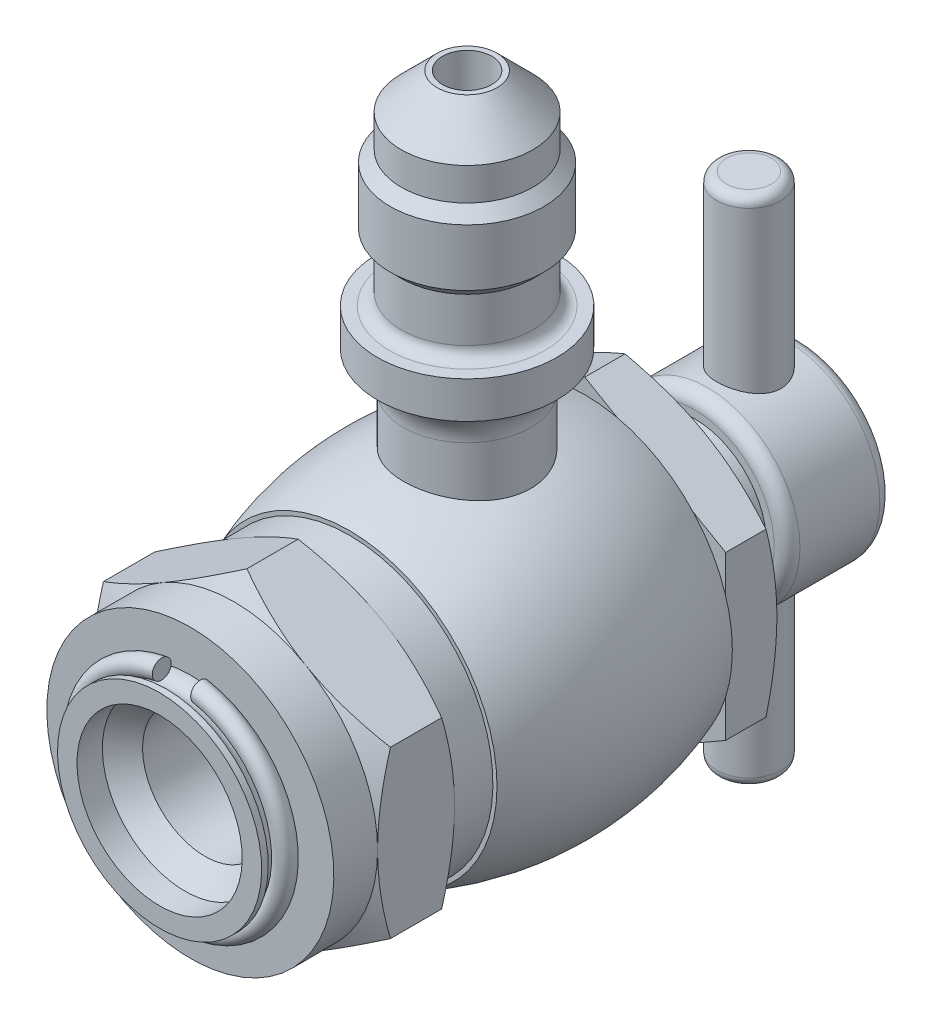
SolidWorks part; units mm, degrees
material "Brass"
ref_plane "Front Plane" through (0, 0, 0) normal (0, 0, 1) x (1, 0, 0)
ref_plane "Top Plane" through (0, 0, 0) normal (0, 1, 0) x (1, 0, 0)
ref_plane "Right Plane" through (0, 0, 0) normal (1, 0, 0) x (0, 0, -1)
sketch "Sketch1" plane through (0, 0, 0) normal (1, 0, 0) x (0, 0, -1)
  line L0 (-19.05, 0) -> (0, 0) construction
  line L1 (0, 0) -> (17.4625, 0) construction
  line L2 (0, 22.9425) -> (0, -22.9425) construction
  line L3 (4.7625, 22.9426) -> (-4.7625, 22.9426) construction
  line L5 (4.7625, 22.9426) -> (4.7625, 24.0009) construction
  line L8 (-3.937, 5.7468) -> (3.937, 5.7468)
  line L9 (5.5563, 8.0328) -> (5.5563, 10.3188)
  line L14 (5.5563, 8.0328) -> (-5.5562, 8.0328)
  line L16 (5.5563, 10.3188) -> (-5.5562, 10.3187)
  line L17 (-5.5562, 8.0328) -> (-5.5562, 10.3187)
  line L18 (0, 8.0328) -> (0, 5.7468) construction
  line L19 (3.937, 5.7468) -> (3.937, 2.8583) construction
  line L21 (19.4469, -22.9426) -> (15.4781, -22.9426)
  line L22 (19.4469, -22.9426) -> (19.4469, 8.8074)
  line L23 (15.4781, -22.9426) -> (15.4781, 8.8074)
  line L24 (19.4469, 8.8074) -> (15.4781, 8.8074)
  line L25 (-19.05, -0.9144) -> (-18.644, -0.9144)
  line L26 (20.6375, -12.6238) -> (20.6375, -1.5113) construction
  line L27 (20.6375, -1.5113) -> (14.097, -1.5113) construction
  line L28 (14.097, -1.5113) -> (14.097, -7.0676) construction
  line L29 (14.097, -7.0676) -> (11.557, -7.0675) construction
  line L30 (11.557, -7.0675) -> (11.557, -0.7179) construction
  line L31 (11.557, -0.7179) -> (9.7467, 2.921) construction
  line L32 (9.7467, 2.921) -> (7.2898, 2.921) construction
  line L33 (7.2898, 2.921) -> (7.2898, -7.239) construction
  line L34 (7.2898, -7.239) -> (-7.2898, -7.239) construction
  line L35 (-7.2898, -7.239) -> (-7.2898, 1.9037) construction
  line L36 (-7.2898, 1.9037) -> (7.2898, 1.9037) construction
  line L37 (-7.2898, -7.239) -> (-9.671, -7.239) construction
  line L38 (-9.671, -7.239) -> (-9.671, 1.651) construction
  line L39 (-9.671, 1.651) -> (-7.2898, 1.651) construction
  line L40 (-9.671, 1.651) -> (-14.4335, 1.651) construction
  line L41 (-14.4335, 1.651) -> (-17.145, 1.651)
  line L42 (-17.145, 1.651) -> (-17.145, -0.9144)
  line L45 (-19.05, -0.9144) -> (-19.05, -7.239)
  line L46 (-19.05, -0.9144) -> (-19.8437, -0.9144) construction
  line L47 (11.5252, 0) -> (-11.5252, 0) construction
  line L48 (0, 11.5252) -> (0, -11.5252) construction
  line L49 (14.097, -7.0676) -> (15.4781, -7.0676) construction
  line L50 (-17.4752, -2.1209) -> (-19.05, -2.1209)
  line L51 (-11.4808, -3.3655) -> (-11.4808, -4.8514)
  line L52 (-9.779, -4.8514) -> (-9.779, -6.35)
  line L53 (-8.1788, -7.239) -> (-8.1788, -6.35)
  line L54 (-8.1788, -6.35) -> (-9.779, -6.35)
  line L55 (-9.779, -4.8514) -> (-11.4808, -4.8514)
  line L56 (-11.4808, -3.3655) -> (-16.2306, -3.3655)
  line L57 (-16.2306, -3.3655) -> (-17.4752, -2.1209)
  line L58 (-8.1788, -7.239) -> (-19.05, -7.239) construction
  line L59 (-19.05, -7.239) -> (-19.05, -2.1209) construction
  line L60 (1.8542, 22.9426) -> (4.0751, 20.7217) construction
  line L61 (4.0751, 20.7217) -> (4.0751, 18.7074) construction
  line L62 (4.0751, 18.7074) -> (4.7625, 18.02) construction
  line L63 (4.7625, 18.02) -> (4.7625, 14.4977) construction
  line L64 (4.7625, 14.4977) -> (4.0751, 13.8103) construction
  line L65 (4.0751, 13.8103) -> (4.0751, 10.3188) construction
  line L66 (4.8771, 23.9347) -> (3.9605, 23.4056) construction
  line L67 (3.9605, 23.4056) -> (4.8771, 22.8764) construction
  line L68 (4.8771, 22.8764) -> (4.8771, 23.9347) construction
  line L69 (4.7625, 23.8686) -> (4.7625, 22.9426) construction
  line L70 (4.8771, 23.4056) -> (4.7625, 23.4056) construction
  line L71 (4.7625, 23.4056) -> (4.0751, 23.4056) construction
  line L72 (4.0751, 23.4056) -> (3.9605, 23.4056) construction
  line L73 (4.0751, 23.4717) -> (4.0751, 23.3394)
  line L74 (4.8198, 23.9017) -> (4.8198, 22.9095)
  line L75 (4.0751, 23.3394) -> (4.8198, 22.9095)
  line L76 (4.0751, 23.4717) -> (4.8198, 23.9017)
  line L77 (-11.4808, -11.1125) -> (-11.4808, -9.6266) construction
  line L78 (-11.4808, -11.1125) -> (-16.2306, -11.1125) construction
  line L79 (-17.4752, -12.3571) -> (-19.05, -12.3571) construction
  line L80 (-16.2306, -11.1125) -> (-17.4752, -12.3571) construction
  arc A1 (7.2898, 1.9037) -> (-7.2898, 1.9037) centre (0, -17.3355) ccw
  arc A2 (-17.145, -0.9144) -> (-18.644, -0.9144) centre (-17.8945, -0.6731) cw
  circle A3 centre (-17.7292, -0.7913) radius 0.5842
  point P0 (0, 1.9037)
  point P23 (17.4625, 8.8074)
  point P89 (20.6375, -7.0676)
  point P92 (4.8198, 23.4056)
  point P98 (0, 3.2385)
  dimension "D23" = 7.239
  dimension "D15" = 20.574
  dimension "D27" = 0.7874
  dimension "D30" = 5.7785
  dimension "D31" = 0.7366
  dimension "D4" = 1.4859
  dimension "D5" = 6.5405
  dimension "D6" = 2.54
  dimension "D7" = 4.2672
  dimension "D8" = 10.16
  dimension "D9" = 20.955
  dimension "D10" = 2.3813
  dimension "D11" = 8.89
  dimension "D12" = 63.55
  dimension "D13" = 6.3497
  dimension "D14" = 7.874
  dimension "D16" = 2.286
  dimension "D17" = 2.286
  dimension "D18" = 45
  dimension "D19" = 11.1125
  dimension "D20" = 3.7084
  dimension "D21" = 2.0142
  dimension "D22" = 135
  dimension "D24" = 4.7625
  dimension "D25" = 1.905
  dimension "D26" = 12.6492
  dimension "D28" = 3.175
  dimension "D29" = 11.1125
  dimension "CL of Handle" = 36.5125
  dimension "CL of Valve" = 19.05
  dimension "Handle Length" = 31.75
  dimension "Handle Dia" = 3.9688
  dimension "Thread 2 OD" = 9.525
  dimension "Pitch 2" = 1.0583
  dimension "Thread Engage" = 12.6238
  dimension "D32" = 1.5748
  dimension "Thead Pitch 1" = 0.7937
  dimension "D33" = 135
  dimension "Thread 1 OD" = 7.747
  dimension "D35" = 10.2362
  dimension "D36" = 1.7018
  dimension "D37" = 1.778
  dimension "D38" = 1.6002
  dimension "D39" = 10.8712
  dimension "D40" = 30.1816
  dimension "D41" = 4.8971
  dimension "D42" = 1.0583
  dimension "D43" = 0.1323
sketch "Sketch2" plane through (0, 0, 0) normal (1, 0, 0) x (0, 0, -1)
  line L0 (-14.4335, 1.651) -> (-17.145, 1.651) construction
  line L1 (-17.145, 1.651) -> (-17.145, -0.9144) construction
  line L2 (-17.4752, -2.1209) -> (-19.05, -2.1209) construction
  line L3 (7.2898, -7.239) -> (-7.2898, -7.239) construction
  line L4 (-19.05, -0.9144) -> (-19.05, -7.239) construction
  line L5 (-7.2898, 1.651) -> (-17.145, 1.651)
  line L6 (-17.145, 1.651) -> (-17.145, -0.9144)
  line L9 (-19.05, -0.9144) -> (-19.05, -2.1209)
  line L10 (11.557, -7.0675) -> (11.557, -0.7179) construction
  line L11 (11.557, -0.7179) -> (9.7467, 2.921) construction
  line L12 (9.7467, 2.921) -> (7.2898, 2.921) construction
  line L13 (7.2898, 2.921) -> (7.2898, -7.239) construction
  line L14 (-7.2898, -7.239) -> (-7.2898, 1.9037) construction
  line L15 (11.557, -2.794) -> (11.557, -0.7179)
  line L16 (11.557, -0.7179) -> (9.7467, 2.921)
  line L17 (9.7467, 2.921) -> (7.2898, 2.921)
  line L18 (7.2898, 2.921) -> (7.2898, 1.9037)
  line L19 (-7.2898, 1.651) -> (-7.2898, 1.9037)
  line L20 (11.557, -2.794) -> (14.097, -2.794)
  line L21 (14.097, -2.794) -> (14.097, -1.5113)
  line L22 (14.097, -1.5113) -> (20.6375, -1.5113)
  line L23 (20.6375, -1.5113) -> (20.6375, -7.239)
  line L24 (20.6375, -7.239) -> (-8.1788, -7.239)
  line L25 (20.6375, -12.6238) -> (20.6375, -1.5113) construction
  line L26 (-17.4752, -2.1209) -> (-19.05, -2.1209)
  line L27 (-11.4808, -3.3655) -> (-11.4808, -4.8514)
  line L28 (-9.779, -4.8514) -> (-9.779, -6.35)
  line L29 (-8.1788, -7.239) -> (-8.1788, -6.35)
  line L30 (-8.1788, -6.35) -> (-9.779, -6.35)
  line L31 (-9.779, -4.8514) -> (-11.4808, -4.8514)
  line L32 (-11.4808, -3.3655) -> (-16.2306, -3.3655)
  line L33 (-16.2306, -3.3655) -> (-17.4752, -2.1209)
  line L34 (-8.1788, -7.239) -> (-19.05, -7.239) construction
  line L35 (-19.05, -7.239) -> (-19.05, -2.1209) construction
  line L37 (-19.05, -0.9144) -> (-18.644, -0.9144) construction
  line L38 (-19.05, -0.9144) -> (-18.644, -0.9144)
  line L40 (-11.4808, -3.3655) -> (-16.2306, -3.3655) construction
  line L41 (-16.2306, -3.3655) -> (-17.4752, -2.1209) construction
  line L42 (-11.4808, -3.3655) -> (-11.4808, -4.8514) construction
  line L43 (-9.779, -4.8514) -> (-11.4808, -4.8514) construction
  line L44 (-9.779, -4.8514) -> (-9.779, -6.35) construction
  line L45 (-8.1788, -6.35) -> (-9.779, -6.35) construction
  line L46 (-8.1788, -7.239) -> (-8.1788, -6.35) construction
  arc A0 (7.2898, 1.9037) -> (-7.2898, 1.9037) centre (0, -17.3355) ccw construction
  arc A1 (7.2898, 1.9037) -> (-7.2898, 1.9037) centre (0, -17.3355) ccw
  arc A2 (-18.644, -0.9144) -> (-17.145, -0.9144) centre (-17.8945, -0.6731) ccw construction
  arc A3 (-18.644, -0.9144) -> (-17.145, -0.9144) centre (-17.8945, -0.6731) ccw
  dimension "D1" = 4.445
  dimension "D10" = 1.5748
revolve "Revolve1" add sketch "Sketch2" angle 360 about L24
cosmetic thread "Cosmetic Thread1" parameters "D2"=9.525
sketch "Sketch3" plane through (0, 0, -7.2898) normal (0, 0, 1) x (1, 0, 0)
  line L1 (8.7312, -12.28) -> (8.7312, -2.198)
  line L2 (8.7312, -2.198) -> (0, 2.843)
  line L3 (0, 2.843) -> (-8.7312, -2.198)
  line L4 (-8.7312, -2.198) -> (-8.7312, -12.28)
  line L5 (-8.7312, -12.28) -> (0, -17.321)
  line L6 (0, -17.321) -> (8.7312, -12.28)
  circle A0 centre (0, -7.239) radius 8.7312 construction
  circle A3 centre (0, -7.239) radius 10.4775 construction
  dimension "D1" = 17.4625
extrude "Cut-Extrude1" cut sketch "Sketch3" against normal up to surface (4.2672 mm away) flip side to cut up to face at (0, -0.7179, -11.557)
sketch "Sketch4" plane through (0, 0, 17.145) normal (0, 0, 1) x (1, 0, 0)
  line L1 (8.89, -12.3716) -> (8.89, -2.1064)
  line L2 (8.89, -2.1064) -> (0, 3.0263)
  line L3 (0, 3.0263) -> (-8.89, -2.1064)
  line L4 (-8.89, -2.1064) -> (-8.89, -12.3716)
  line L5 (-8.89, -12.3716) -> (0, -17.5043)
  line L6 (0, -17.5043) -> (8.89, -12.3716)
  circle A0 centre (0, -7.239) radius 8.89 construction
  circle A1 centre (0, -7.239) radius 8.89 construction
  circle A2 centre (0, -7.239) radius 5.1181 construction
  circle A3 centre (0, -7.239) radius 5.1181
extrude "Boss-Extrude1" add sketch "Sketch4" along normal up to vertex (-2.7115 mm away) from vertex at -7.474 starting at point (0, 1.651, 9.671)
sketch "Sketch5" plane through (0, 0, 0) normal (1, 0, 0) x (0, 0, -1)
  line L0 (-14.4335, 1.651) -> (-12.8455, 4.4016)
  line L1 (-12.8455, 4.4016) -> (-14.4335, 4.4016)
  line L2 (-14.4335, 4.4016) -> (-14.4335, 1.651)
  line L3 (-12.0523, 3.0263) -> (-12.0523, 4.4016) construction
  line L4 (-14.4335, 3.0263) -> (-9.671, 3.0263) construction
  line L5 (-9.671, 4.4016) -> (-9.671, 1.651)
  line L6 (-11.2591, 4.4016) -> (-9.671, 4.4016)
  line L7 (-9.671, 1.651) -> (-11.2591, 4.4016)
  dimension "D1" = 30
revolve "Cut-Revolve1" cut sketch "Sketch5" angle 360 about L34
fillet "Fillet1" radius 0.795 2 edges at (0, -1.5113, -14.097) (0, -1.5113, -20.6375)
sketch "Sketch6" plane through (0, 0, 0) normal (0, 1, 0) x (1, 0, 0)
  circle A0 centre (0, 17.4625) radius 1.9844
extrude "Cut-Extrude2" cut sketch "Sketch6" against normal through all
sketch "Sketch7" plane through (0, 0, 0) normal (1, 0, 0) x (0, 0, -1)
  line L0 (17.4625, 8.8074) -> (17.4625, -22.9426)
  line L1 (17.4625, 8.8074) -> (18.8516, 8.8074)
  line L2 (17.4625, -22.9426) -> (18.8516, -22.9426)
  line L3 (19.4469, 8.2121) -> (19.4469, -22.3472)
  arc A0 (18.8516, -22.9426) -> (19.4469, -22.3472) centre (18.8516, -22.3472) ccw
  arc A1 (18.8516, 8.8074) -> (19.4469, 8.2121) centre (18.8516, 8.2121) cw
  point P9 (19.4469, -22.9426)
  dimension "D1" = 0.5953
revolve "Revolve2" add sketch "Sketch7" angle 360 about L0
sketch "Sketch8" plane through (0, 0, 0) normal (1, 0, 0) x (0, 0, -1)
  line L0 (-3.937, 5.7468) -> (3.937, 5.7468) construction
  line L1 (3.937, 5.7468) -> (3.937, 2.8583) construction
  line L2 (5.5563, 8.0328) -> (-5.5562, 8.0328) construction
  line L3 (5.5563, 8.0328) -> (5.5563, 10.3188) construction
  line L9 (1.524, 5.7468) -> (3.937, 5.7468) construction
  line L10 (3.937, 5.7468) -> (3.937, -7.239)
  line L11 (5.5563, 8.0328) -> (1.524, 8.0328) construction
  line L12 (5.5563, 8.0328) -> (5.5563, 10.3188)
  line L18 (3.937, -7.239) -> (1.524, -7.239)
  line L19 (0, 22.9425) -> (0, -22.9425) construction
  line L20 (0, -7.239) -> (0, 22.9425) construction
  line L22 (7.2898, -7.239) -> (-7.2898, -7.239) construction
  line L23 (1.524, 22.9426) -> (1.524, -7.239)
  line L24 (4.7625, 22.9426) -> (-4.7625, 22.9426) construction
  line L25 (4.0751, 13.8103) -> (4.0751, 10.3188) construction
  line L26 (4.7625, 14.4977) -> (4.0751, 13.8103) construction
  line L27 (4.7625, 18.02) -> (4.7625, 14.4977) construction
  line L28 (4.0751, 18.7074) -> (4.7625, 18.02) construction
  line L29 (4.0751, 20.7217) -> (4.0751, 18.7074) construction
  line L30 (1.8542, 22.9426) -> (4.0751, 20.7217) construction
  line L31 (4.0751, 13.8103) -> (4.0751, 11.0593)
  line L32 (4.7625, 14.4977) -> (4.0751, 13.8103)
  line L33 (4.7625, 18.02) -> (4.7625, 14.4977)
  line L34 (4.0751, 18.7074) -> (4.7625, 18.02)
  line L35 (4.0751, 20.7217) -> (4.0751, 18.7074)
  line L36 (1.8542, 22.9426) -> (4.0751, 20.7217)
  line L37 (1.524, 22.9426) -> (1.8542, 22.9426)
  line L38 (4.8157, 10.3187) -> (5.5563, 10.3188)
  line L39 (4.8157, 10.3187) -> (4.0751, 10.3188) construction
  arc A0 (3.937, 5.7468) -> (5.5563, 8.0328) centre (6.3603, 5.7468) cw
  arc A1 (4.0751, 11.0593) -> (4.8157, 10.3187) centre (4.8157, 11.0593) ccw
  dimension "D1" = 3.048
revolve "Revolve3" add sketch "Sketch8" angle 360 about L20
cosmetic thread "Cosmetic Thread2" parameters "D2"=8.2652
sketch "Sketch20" plane through (0, 0, 0) normal (1, 0, 0) x (0, 0, -1)
  line L1 (-7.2898, 5.7468) -> (-7.2898, -22.3472)
  line L2 (7.2898, 5.7468) -> (7.2898, -22.3472)
  line L3 (-7.2898, -22.3472) -> (7.2898, -22.3472)
  line L4 (15.4781, -22.3472) -> (19.4469, -22.3472) construction
  line L5 (7.2898, -13.4445) -> (7.2898, -16.1565) construction
  line L6 (-7.2898, 1.9037) -> (-7.2898, -16.3817) construction
  line L7 (7.2898, 5.7468) -> (11.557, 5.7468)
  line L8 (11.557, 5.7468) -> (11.557, -22.3472)
  line L9 (11.557, -13.7601) -> (11.557, -0.7179) construction
  line L10 (3.937, 5.7468) -> (-3.937, 5.7468) construction
split "Split2" trim tools "Sketch20" bodies to split 110 resulting bodies 122 123 124 125
sketch "Sketch10" plane through (0, 0, 0) normal (1, 0, 0) x (0, 0, -1)
  circle A0 centre (-17.7292, -0.7913) radius 0.5842 construction
  circle A1 centre (-17.7292, -0.7913) radius 0.5842
revolve "Revolve4" add sketch "Sketch10" angle 360 about L37
sketch "Sketch11" plane through (0, 0, 19.05) normal (0, 0, 1) x (1, 0, 0)
  line L0 (-1.1906, 1.5709) -> (1.1906, 1.5709)
  line L1 (-1.1906, 1.5709) -> (-1.1906, -2.1209)
  line L2 (1.1906, 1.5709) -> (1.1906, -2.1209)
  line L3 (-1.1906, -2.1209) -> (1.1906, -2.1209)
  circle A0 centre (0, -7.239) radius 5.1181 construction
  circle A1 centre (0, -7.239) radius 8.89 construction
  point P9 (0, -2.1209)
  dimension "D1" = 2.3813
extrude "Cut-Extrude4" cut sketch "Sketch11" against normal blind 5.334
